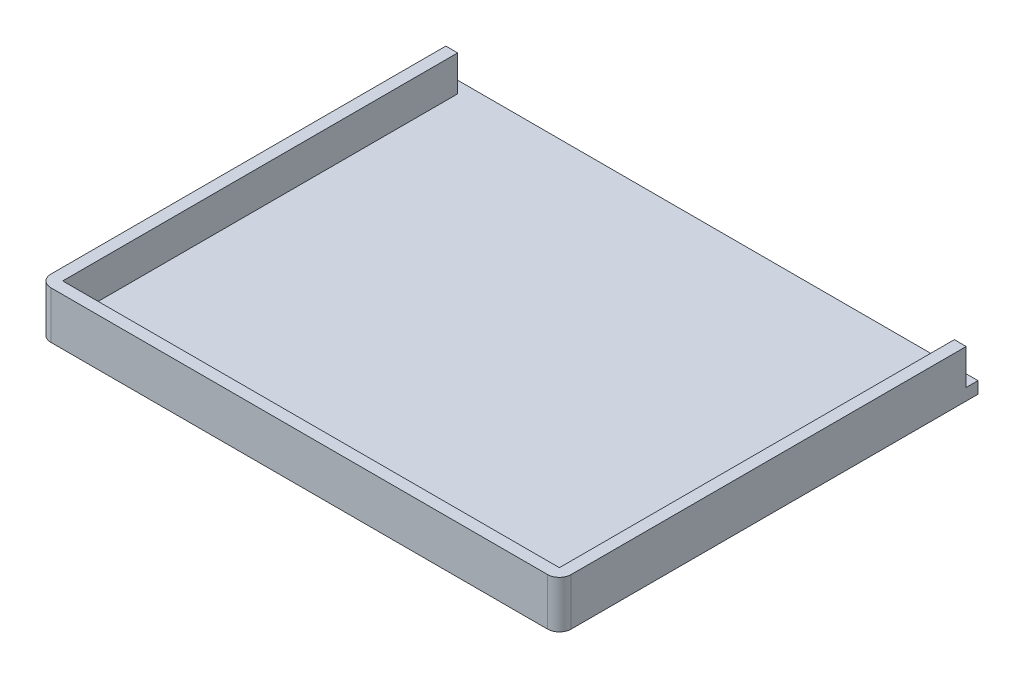
SolidWorks part; units mm, degrees
ref_plane "Front Plane" through (0, 0, 0) normal (0, 0, 1) x (1, 0, 0)
ref_plane "Top Plane" through (0, 0, 0) normal (0, 1, 0) x (1, 0, 0)
ref_plane "Right Plane" through (0, 0, 0) normal (1, 0, 0) x (0, 0, -1)
sketch "Sketch1" plane through (0, 0, 0) normal (0, 1, 0) x (1, 0, 0)
  line L1 (-110, 88.5) -> (110, 88.5)
  line L2 (-110, 88.5) -> (-110, -88.5)
  line L3 (-110, -88.5) -> (110, -88.5)
  line L4 (110, 88.5) -> (110, -88.5)
  line L5 (-110, 88.5) -> (110, -88.5) construction
  line L6 (-110, -88.5) -> (110, 88.5) construction
  point P0 (0, 0)
  dimension "D1" = 220
  dimension "D2" = 177
extrude "Boss-Extrude1" add sketch "Sketch1" along normal blind 5
fillet "Fillet1" radius 5 2 edges at (110, 2.5, 88.5) (-110, 2.5, 88.5)
sketch "Sketch3" plane through (0, 5, 0) normal (0, 1, 0) x (1, 0, 0)
  line L0 (-105, 83.5) -> (-105, -83.5)
  line L1 (-105, -83.5) -> (105, -83.5)
  line L2 (105, -83.5) -> (105, 83.5)
  line L4 (-105, -88.5) -> (105, -88.5)
  line L5 (110, -83.5) -> (110, 88.5)
  line L6 (110, 88.5) -> (-110, 88.5)
  line L7 (-110, 88.5) -> (-110, -83.5)
  line L8 (-105, -88.5) -> (105, -88.5)
  line L9 (110, -83.5) -> (110, 83.5)
  line L11 (-110, 83.5) -> (-110, -83.5)
  line L12 (105, 83.5) -> (-105, 83.5) construction
  line L13 (110, 88.5) -> (-110, 88.5) construction
  line L14 (110, 83.5) -> (105, 83.5)
  line L15 (-105, 83.5) -> (-110, 83.5)
  line L16 (110, -83.5) -> (110, 88.5) construction
  line L17 (-110, 88.5) -> (-110, -83.5) construction
  arc A0 (-105, -83.5) -> (-105, -83.5) centre (-105, -83.5) ccw
  arc A1 (105, -83.5) -> (105, -83.5) centre (105, -83.5) ccw
  arc A2 (105, -88.5) -> (110, -83.5) centre (105, -83.5) ccw
  arc A3 (-110, -83.5) -> (-105, -88.5) centre (-105, -83.5) ccw
  arc A4 (105, -88.5) -> (110, -83.5) centre (105, -83.5) ccw
  arc A5 (-110, -83.5) -> (-105, -88.5) centre (-105, -83.5) ccw
  dimension "D1" = 0
  dimension "D2" = 5
extrude "Boss-Extrude2" add sketch "Sketch3" along normal blind 15
